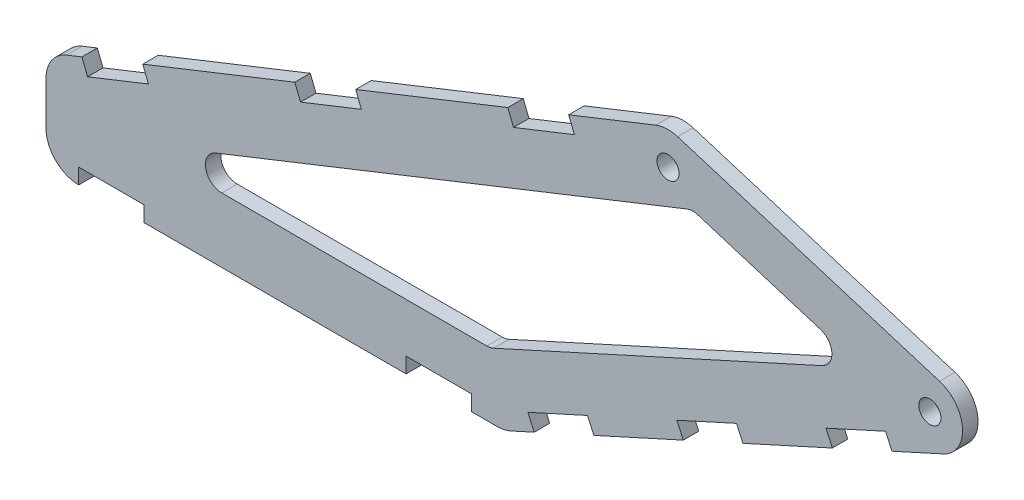
SolidWorks part; units mm, degrees
material "Custom Plastic"
ref_plane "Front Plane" through (0, 0, 0) normal (0, 0, 1) x (1, 0, 0)
ref_plane "Top Plane" through (0, 0, 0) normal (0, 1, 0) x (1, 0, 0)
ref_plane "Right Plane" through (0, 0, 0) normal (1, 0, 0) x (0, 0, -1)
sketch "Sketch1" plane through (0, 0, 0) normal (0, 0, 1) x (1, 0, 0)
  line L0 (76.2, 0) -> (76.2, 41.0718) construction
  line L1 (0, 0) -> (127, 0) construction
  line L2 (127, 0) -> (127, 25.4) construction
  dimension "D1" = 127
  dimension "D2" = 25.4
  dimension "D3" = 41.0718
  dimension "D4" = 76.2
sketch "Sketch2" plane through (0, 0, 0) normal (0, 0, 1) x (1, 0, 0)
  line L1 (-44.45, -19.05) -> (44.45, -19.05)
  line L2 (78.0719, 47.1396) -> (128.8719, 31.4678)
  line L3 (-44.45, 0) -> (73.8567, 46.9736)
  line L4 (44.45, -19.05) -> (129.625, 19.6179)
  line L5 (-44.45, 0) -> (-44.45, -19.05)
  arc A0 (78.0719, 47.1396) -> (73.8567, 46.9736) centre (76.2, 41.0718) ccw
  arc A1 (129.625, 19.6179) -> (128.8719, 31.4678) centre (127, 25.4) ccw
  point P10 (-44.45, -19.05)
  point P12 (44.45, -19.05)
  point P17 (-44.45, 0)
  point P19 (0, -19.05)
  dimension "D1" = 6.35
  dimension "D5" = 19.05
  dimension "D8" = 88.9
extrude "Base" add sketch "Sketch2" along normal blind 2.9972
hole_wizard "Joint holes" positions "Sketch4" profile "Sketch3" hole size "#8" standard "ANSI Inch"
sketch "Sketch4" plane through (0, 0, 2.9972) normal (0, 0, 1) x (1, 0, 0)
  point P0 (76.2, 41.0718)
  point P3 (127, 25.4)
sketch "Sketch3" plane through (76.2, 41.0718, 2.9972) normal (1, 0, 0) x (0, -1, 0)
  line L0 (0, 0) -> (0, 6.351)
  line L1 (0, 6.351) -> (2.1526, 6.351)
  line L2 (2.1526, 6.351) -> (2.1526, 0)
  line L5 (2.1526, 0) -> (0, 0)
  line L10 (0, 6.351) -> (-2.1526, 6.351) construction
  line L11 (0, -6.35) -> (0, 107.95) construction
  dimension "Hole Dia." = 4.3053
  dimension "Hole Depth" = 6.351
  dimension "Drill Angle" = 180
fillet "Outer fillet" radius 6.35 3 edges at (44.45, -19.05, 1.4986) (-44.45, -19.05, 1.4986) (-44.45, 0, 1.4986)
sketch "Sketch5" plane through (0, 0, 2.9972) normal (0, 0, 1) x (1, 0, 0)
  line L0 (-38.1, -19.05) -> (43.0761, -19.05) construction
  line L1 (-38.1, -19.05) -> (-25.4, -19.05)
  line L2 (-38.1, -19.05) -> (-38.1, -16.0528)
  line L3 (-38.1, -16.0528) -> (-25.4, -16.0528)
  line L4 (-25.4, -19.05) -> (-25.4, -16.0528)
  line L6 (25.4, -19.05) -> (38.1, -19.05)
  line L7 (25.4, -19.05) -> (25.4, -16.0528)
  line L8 (25.4, -16.0528) -> (38.1, -16.0528)
  line L9 (38.1, -19.05) -> (38.1, -16.0528)
  dimension "D1" = 12.7
  dimension "D2" = 25.4
  dimension "D3" = 2.9972
  dimension "D4" = 25.4
extrude "Base plate slots" cut sketch "Sketch5" against normal through all
sketch "Sketch6" plane through (0, 0, 2.9972) normal (0, 0, 1) x (1, 0, 0)
  line L0 (50.2603, -16.4122) -> (49.0214, -13.6831)
  line L1 (45.701, -18.4821) -> (129.625, 19.6179) construction
  line L2 (49.0214, -13.6831) -> (60.5855, -8.4332)
  line L3 (60.5855, -8.4332) -> (61.8245, -11.1623)
  line L4 (50.2603, -16.4122) -> (61.8245, -11.1623)
  line L5 (79.1706, -3.2874) -> (77.9316, -0.5583)
  line L6 (77.9316, -0.5583) -> (89.4957, 4.6916)
  line L7 (89.4957, 4.6916) -> (90.7347, 1.9625)
  line L8 (79.1706, -3.2874) -> (90.7347, 1.9625)
  line L9 (108.0809, 9.8373) -> (106.8419, 12.5664)
  line L10 (106.8419, 12.5664) -> (118.406, 17.8163)
  line L11 (118.406, 17.8163) -> (119.645, 15.0872)
  line L12 (108.0809, 9.8373) -> (119.645, 15.0872)
  arc A0 (43.0761, -19.05) -> (45.701, -18.4821) centre (43.0761, -12.7) ccw construction
  point P4 (44.4189, -18.9064)
  point P10 (0, 0)
  dimension "D1" = 2.9972
  dimension "D2" = 12.7
  dimension "D3" = 6.35
  dimension "D4" = 3
  dimension "D5" = 31.75
extrude "Under plate slots" cut sketch "Sketch6" against normal through all
sketch "Sketch7" plane through (0, 0, 2.9972) normal (0, 0, 1) x (1, 0, 0)
  line L0 (-37.4924, 2.7625) -> (-36.3864, -0.0231)
  line L1 (73.8567, 46.9736) -> (-40.4433, 1.5909) construction
  line L2 (-36.3864, -0.0231) -> (-24.5827, 4.6635)
  line L3 (-24.5827, 4.6635) -> (-25.6888, 7.4491)
  line L4 (-37.4924, 2.7625) -> (-25.6888, 7.4491)
  line L6 (3.8203, 19.1657) -> (4.9263, 16.38)
  line L7 (4.9263, 16.38) -> (16.7299, 21.0667)
  line L8 (16.7299, 21.0667) -> (15.6239, 23.8523)
  line L9 (3.8203, 19.1657) -> (15.6239, 23.8523)
  line L11 (45.133, 35.5689) -> (46.239, 32.7832)
  line L12 (46.239, 32.7832) -> (58.0426, 37.4698)
  line L13 (58.0426, 37.4698) -> (56.9366, 40.2555)
  line L14 (45.133, 35.5689) -> (56.9366, 40.2555)
  dimension "D1" = 2.9972
  dimension "D2" = 12.7
  dimension "D3" = 3.175
  dimension "D5" = 44.45
  dimension "D4" = 3
extrude "Top plate slots" cut sketch "Sketch7" against normal through all
sketch "Sketch8" plane through (0, 0, 2.9972) normal (0, 0, 1) x (1, 0, 0)
  line L0 (-26.9576, -6.5278) -> (80.9031, 36.2982)
  line L1 (-26.9576, -6.5278) -> (41.7406, -6.5278)
  line L2 (41.7406, -6.5278) -> (113.7523, 26.1643)
  line L3 (3.8203, 19.1657) -> (-25.6888, 7.4491) construction
  line L4 (-25.4, -19.05) -> (25.4, -19.05) construction
  line L5 (61.8245, -11.1623) -> (79.1706, -3.2874) construction
  line L6 (4.9263, 16.38) -> (16.7299, 21.0667) construction
  line L7 (38.1, -16.0528) -> (25.4, -16.0528) construction
  line L8 (60.5855, -8.4332) -> (49.0214, -13.6831) construction
  line L9 (80.9031, 36.2982) -> (113.7523, 26.1643)
  line L10 (128.8719, 31.4678) -> (78.0719, 47.1396) construction
  dimension "D1" = 9.525
  dimension "D2" = 9.525
  dimension "D3" = 9.525
  dimension "D4" = 9.525
extrude "Inner hole" cut sketch "Sketch8" against normal through all
fillet "Inner fillet" radius 3.175 4 edges at (-26.9576, -6.5278, 1.4986) (113.7523, 26.1643, 1.4986) (41.7406, -6.5278, 1.4986) (80.9031, 36.2982, 1.4986)
